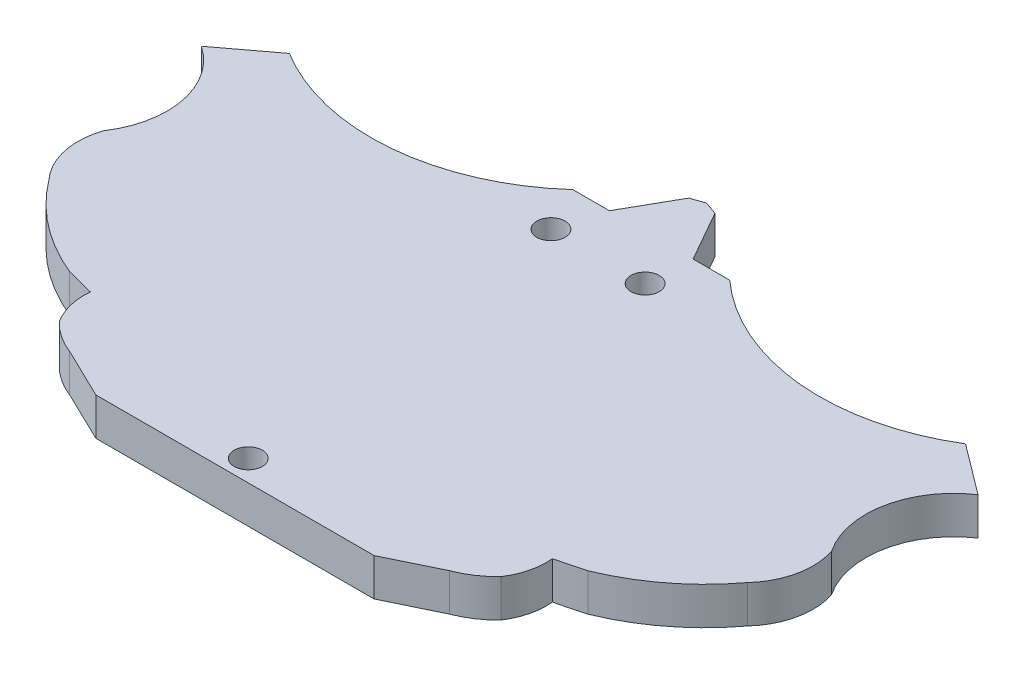
SolidWorks part; units mm, degrees
ref_plane "Front Plane" through (0, 0, 0) normal (0, 0, 1) x (1, 0, 0)
ref_plane "Top Plane" through (0, 0, 0) normal (0, 1, 0) x (1, 0, 0)
ref_plane "Right Plane" through (0, 0, 0) normal (1, 0, 0) x (0, 0, -1)
sketch "Sketch3" plane through (0, 0, 0) normal (0, 1, 0) x (1, 0, 0)
  line L0 (84.4541, 599.5572) -> (574.4541, 599.5572) construction
sketch "Sketch2" plane through (0, 0, 0) normal (0, 1, 0) x (1, 0, 0)
  line L0 (0, 0) -> (0, 57.603) construction
  line L1 (-18.1438, -7.9279) -> (18.1438, -7.9279) construction
  line L2 (-18.1438, -7.9279) -> (-18.1438, 7.9279) construction
  line L3 (-18.1438, 7.9279) -> (18.1438, 7.9279) construction
  line L4 (18.1438, -7.9279) -> (18.1438, 7.9279) construction
  line L5 (-18.1438, -7.9279) -> (18.1438, 7.9279) construction
  line L6 (-18.1438, 7.9279) -> (18.1438, -7.9279) construction
  line L7 (-21.8576, -11.143) -> (21.8576, -11.143) construction
  line L8 (-21.8576, -11.143) -> (-21.8576, 11.143) construction
  line L9 (-21.8576, 11.143) -> (21.8576, 11.143) construction
  line L10 (21.8576, -11.143) -> (21.8576, 11.143) construction
  line L11 (-21.8576, -11.143) -> (21.8576, 11.143) construction
  line L12 (-21.8576, 11.143) -> (21.8576, -11.143) construction
  line L13 (-8.5, 0) -> (8.5, 0) construction
  line L14 (0, 0) -> (0, -8.8619) construction
  line L15 (-20.6395, 7.1502) -> (-17.9674, 9.1598)
  line L16 (-4.1695, 10.4244) -> (4.1695, 10.4244)
  line L17 (-1.5343, -5.6375) -> (1.5343, -5.6375)
  line L18 (-10.0901, -10.3942) -> (-7.3916, -11.6987)
  line L19 (20.6395, 7.1502) -> (17.9674, 9.1598)
  line L20 (-2.2241, 10.4244) -> (-0.6961, 13.1148)
  line L21 (-0.6961, 13.1148) -> (0, 13.358)
  line L22 (2.2241, 10.4244) -> (0.6961, 13.1148)
  line L23 (0.6961, 13.1148) -> (0, 13.358)
  line L24 (-7.3916, -11.6987) -> (-0.7757, -11.143)
  line L25 (-0.7757, -11.143) -> (0, -10.9595)
  line L26 (0.7757, -11.143) -> (0, -10.9595)
  line L27 (7.3916, -11.6987) -> (0.7757, -11.143)
  line L28 (10.0901, -10.3942) -> (7.3916, -11.6987)
  line L29 (-16.4215, -5.191) -> (-11.7373, -9.2961)
  line L30 (16.4215, -5.191) -> (11.7373, -9.2961)
  line L31 (-7.3916, -11.6987) -> (7.3916, -11.6987)
  line L33 (-32.5, -20.0045) -> (32.5, -20.0045)
  line L34 (-32.5, -20.0045) -> (-32.5, 20.0045)
  line L35 (-32.5, 20.0045) -> (32.5, 20.0045)
  line L36 (32.5, -20.0045) -> (32.5, 20.0045)
  line L37 (-32.5, -20.0045) -> (32.5, 20.0045) construction
  line L38 (-32.5, 20.0045) -> (32.5, -20.0045) construction
  arc A0 (-4.1695, 10.4244) -> (-17.9674, 9.1598) centre (-11.9148, 19.0269) cw
  arc A1 (-20.6395, 7.1502) -> (-19.3461, 0.6629) centre (-23.2364, 3.2599) cw
  arc A2 (-19.3461, 0.6629) -> (-18.559, -3.0217) centre (-15.82, -0.5102) ccw
  arc A3 (-18.559, -3.0217) -> (-13.7831, -6.7121) centre (-9.4985, 3.7682) ccw
  arc A4 (-13.7831, -6.7121) -> (-6.6237, -7.9279) centre (-4.6259, 25.5245) ccw
  arc A5 (-1.5343, -5.6375) -> (-6.6237, -7.9279) centre (-1.5343, -12.4372) ccw
  arc A7 (13.7831, -6.7121) -> (6.6237, -7.9279) centre (4.6259, 25.5245) cw
  arc A8 (18.559, -3.0217) -> (13.7831, -6.7121) centre (9.4985, 3.7682) cw
  arc A9 (19.3461, 0.6629) -> (18.559, -3.0217) centre (15.82, -0.5102) cw
  arc A10 (20.6395, 7.1502) -> (19.3461, 0.6629) centre (23.2364, 3.2599) ccw
  arc A11 (4.1695, 10.4244) -> (17.9674, 9.1598) centre (11.9148, 19.0269) ccw
  arc A12 (1.5343, -5.6375) -> (6.6237, -7.9279) centre (1.5343, -12.4372) cw
  arc A14 (-12.2767, -7.1024) -> (-11.7373, -9.2961) centre (-8.8887, -7.4325) ccw
  arc A15 (-11.7373, -9.2961) -> (-10.0901, -10.3942) centre (-8.5052, -6.2323) ccw
  arc A16 (12.2767, -7.1024) -> (11.7373, -9.2961) centre (8.8887, -7.4325) cw
  arc A17 (11.7373, -9.2961) -> (10.0901, -10.3942) centre (8.5052, -6.2323) cw
  point P0 (0, 0)
  point P6 (0, 0)
  point P34 (0, 0)
  point P45 (0, 10.4244)
  point P54 (0, -5.6375)
  point P57 (-0.2087, -5.6375)
  point P72 (0, -11.6987)
  dimension "D2" = 65
  dimension "D1" = 17
extrude "Boss-Extrude1" add sketch "Sketch2" along normal blind 2
scale "Scale1" bodies to scale 101 scale about centroid uniform scaling yes scale factor 2
sketch "Sketch6" plane through (0, 3, 0) normal (0, 1, 0) x (1, 0, 0)
  line L0 (0, 0) -> (0, 27.4099) construction
  circle A0 centre (-5.8515, 16.2836) radius 1.5 construction
  circle A1 centre (-5.8515, 16.2836) radius 1.5
  circle A2 centre (4.1518, 16.2836) radius 1.5 construction
  circle A3 centre (4.1518, 16.2836) radius 1.5
extrude "Cut-Extrude2" cut sketch "Sketch6" against normal blind 3
sketch "Sketch9" plane through (0, 3, 0) normal (0, 1, 0) x (1, 0, 0)
  line L21 (-7.6951, -21.8709) -> (-7.6951, -30.6829)
  line L22 (-7.6951, -30.6829) -> (5.9954, -30.6829)
  line L23 (5.9954, -30.6829) -> (5.9954, -21.8709)
  line L24 (5.9954, -21.8709) -> (8.9954, -21.8709)
  line L25 (8.9954, -21.8709) -> (8.9954, -30.0705)
  line L26 (8.9954, -30.0705) -> (18.6231, -24.4632)
  line L27 (18.6231, -24.4632) -> (23.9122, -21.0338)
  line L28 (25.28, -18.5167) -> (25.28, -3.348)
  line L29 (24.6327, -1.4865) -> (9.0527, 18.2043)
  line L30 (6.7, 19.3428) -> (3.3097, 19.3428)
  line L31 (3.3097, 19.3428) -> (0.5459, 24.5621)
  line L32 (0.5459, 24.5621) -> (-0.8499, 25.1844)
  line L33 (-0.8499, 25.1844) -> (-2.2456, 24.5621)
  line L34 (-2.2456, 24.5621) -> (-5.0094, 19.3428)
  line L35 (-5.0094, 19.3428) -> (-8.3997, 19.3428)
  line L36 (-10.7524, 18.2043) -> (-26.3324, -1.4865)
  line L37 (-26.9797, -3.348) -> (-26.9797, -18.5167)
  line L38 (-25.6119, -21.0338) -> (-20.3228, -24.4632)
  line L39 (-20.3228, -24.4632) -> (-10.6951, -30.0705)
  line L40 (-10.6951, -30.0705) -> (-10.6951, -21.8709)
  line L41 (-10.6951, -21.8709) -> (-7.6951, -21.8709)
  line L42 (-7.6951, -21.8709) -> (-7.6951, -30.6829)
  line L43 (-7.6951, -30.6829) -> (5.9954, -30.6829)
  line L44 (5.9954, -30.6829) -> (5.9954, -21.8709)
  line L45 (5.9954, -21.8709) -> (8.9954, -21.8709)
  line L46 (8.9954, -21.8709) -> (8.9954, -30.0705)
  line L47 (8.9954, -30.0705) -> (18.6231, -24.4632)
  line L48 (18.6231, -24.4632) -> (23.9122, -21.0338)
  line L49 (25.28, -18.5167) -> (25.28, -3.348)
  line L50 (24.6327, -1.4865) -> (9.0527, 18.2043)
  line L51 (6.7, 19.3428) -> (3.3097, 19.3428)
  line L52 (3.3097, 19.3428) -> (0.5459, 24.5621)
  line L53 (0.5459, 24.5621) -> (-0.8499, 25.1844)
  line L54 (-0.8499, 25.1844) -> (-2.2456, 24.5621)
  line L55 (-2.2456, 24.5621) -> (-5.0094, 19.3428)
  line L56 (-5.0094, 19.3428) -> (-8.3997, 19.3428)
  line L57 (-10.7524, 18.2043) -> (-26.3324, -1.4865)
  line L58 (-26.9797, -3.348) -> (-26.9797, -18.5167)
  line L59 (-25.6119, -21.0338) -> (-20.3228, -24.4632)
  line L60 (-20.3228, -24.4632) -> (-10.6951, -30.0705)
  line L61 (-10.6951, -30.0705) -> (-10.6951, -21.8709)
  line L62 (-10.6951, -21.8709) -> (-7.6951, -21.8709)
  arc A6 (23.9122, -21.0338) -> (25.28, -18.5167) centre (22.28, -18.5167) ccw
  arc A7 (25.28, -3.348) -> (24.6327, -1.4865) centre (22.28, -3.348) ccw
  arc A8 (9.0527, 18.2043) -> (6.7, 19.3428) centre (6.7, 16.3428) ccw
  arc A9 (-8.3997, 19.3428) -> (-10.7524, 18.2043) centre (-8.3997, 16.3428) ccw
  arc A10 (-26.3324, -1.4865) -> (-26.9797, -3.348) centre (-23.9797, -3.348) ccw
  arc A11 (-26.9797, -18.5167) -> (-25.6119, -21.0338) centre (-23.9797, -18.5167) ccw
  arc A12 (23.9122, -21.0338) -> (25.28, -18.5167) centre (22.28, -18.5167) ccw
  arc A13 (25.28, -3.348) -> (24.6327, -1.4865) centre (22.28, -3.348) ccw
  arc A14 (9.0527, 18.2043) -> (6.7, 19.3428) centre (6.7, 16.3428) ccw
  arc A15 (-8.3997, 19.3428) -> (-10.7524, 18.2043) centre (-8.3997, 16.3428) ccw
  arc A16 (-26.3324, -1.4865) -> (-26.9797, -3.348) centre (-23.9797, -3.348) ccw
  arc A17 (-26.9797, -18.5167) -> (-25.6119, -21.0338) centre (-23.9797, -18.5167) ccw
  dimension "D1" = 0
sketch "Sketch10" plane through (0, 3, 0) normal (0, 1, 0) x (1, 0, 0)
  circle A0 centre (-0.8499, -20.8953) radius 1.5 construction
  circle A1 centre (-0.8499, -20.8953) radius 1.5
extrude "Cut-Extrude4" cut sketch "Sketch10" against normal blind 10
